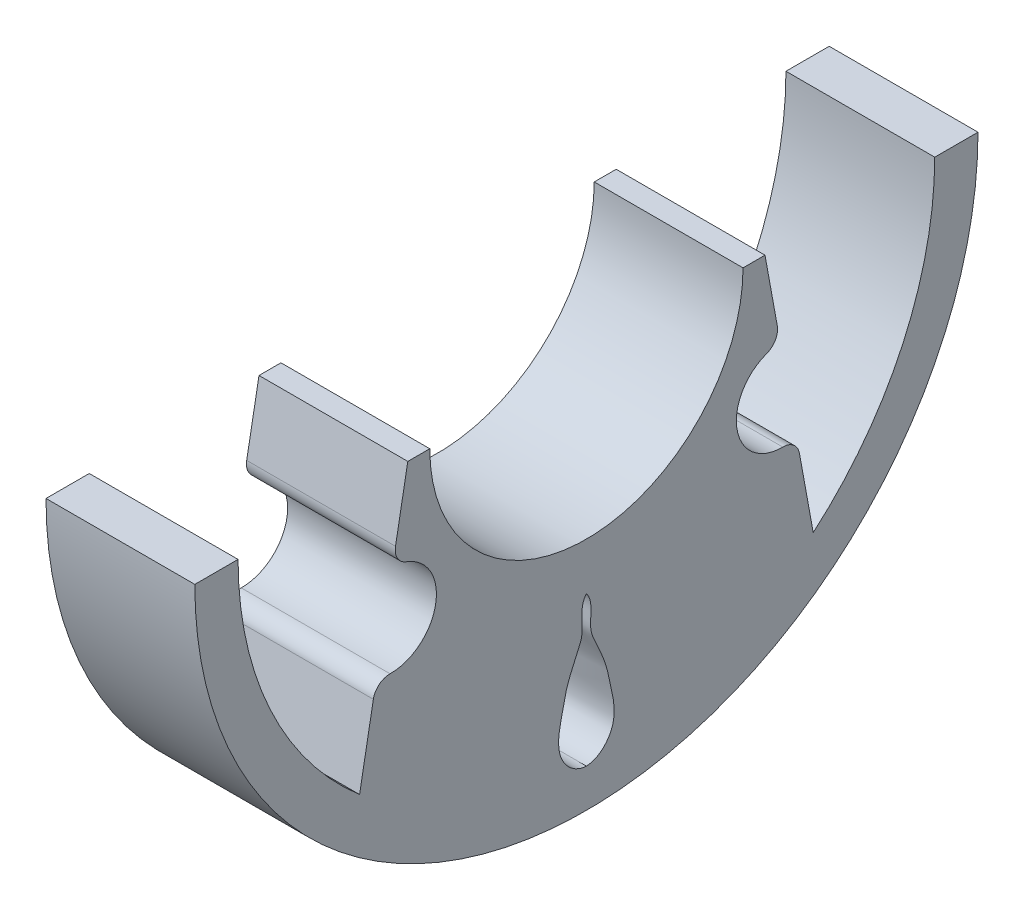
SolidWorks part; units mm, degrees
ref_plane "Front Plane" through (0, 0, 0) normal (0, 0, 1) x (1, 0, 0)
ref_plane "Top Plane" through (0, 0, 0) normal (0, 1, 0) x (1, 0, 0)
ref_plane "Right Plane" through (0, 0, 0) normal (1, 0, 0) x (0, 0, -1)
ref_plane "Plane1" through (0, 0, 0) normal (-1, 0, 0) x (0, -1, 0)
sketch "Sketch1" plane through (0, 0, 0) normal (-1, 0, 0) x (0, -1, 0)
  line L0 (17.2095, 48.7478) -> (0, 45.608)
  line L1 (0, 45.608) -> (0, 40)
  line L2 (0, -40) -> (0, -45.608)
  line L3 (0, -45.608) -> (17.2095, -48.7478)
  line L4 (48.2154, -54.4045) -> (67.5109, -57.9248)
  line L5 (0, -88.955) -> (0, -100)
  line L6 (0, 100) -> (0, 88.955)
  line L7 (67.5109, 57.9248) -> (48.2154, 54.4045)
  arc A0 (22, 45.9999) -> (17.2095, 48.7478) centre (17.9777, 44.5373) ccw
  arc A1 (0, 40) -> (0, -40) centre (0, 0) cw
  arc A2 (17.2095, -48.7478) -> (22, -45.9999) centre (17.9777, -44.5373) ccw
  arc A3 (22, -45.9999) -> (44.7038, -50.142) centre (33, -50) cw
  arc A4 (44.7038, -50.142) -> (48.2154, -54.4045) centre (48.9835, -50.194) ccw
  arc A5 (67.5109, -57.9248) -> (0, -88.955) centre (0, 0) cw
  arc A6 (0, -100) -> (0, 100) centre (0, 0) ccw
  arc A7 (0, 88.955) -> (67.5109, 57.9248) centre (0, 0) cw
  arc A8 (48.2154, 54.4045) -> (44.7038, 50.142) centre (48.9835, 50.194) ccw
  arc A9 (44.7038, 50.142) -> (22, 45.9999) centre (33, 50) cw
  spline S0 degree 3 poles (52, 0) (55.0683, 2.3148) (58.8444, 0.2145) (65.5378, 2.9258) (68.8454, 4.8411) (75.9051, 6.1656) (79.4461, 7.4574) (86.6746, 6.5275) (90.0265, 3.6143) (90.1915, 0) knots 0 0 0 0 0.25 0.25 0.5 0.5 0.75 0.75 1 1 1 1
  spline S1 degree 3 poles (90.1915, 0) (90.0265, -3.6143) (86.6746, -6.5275) (79.4461, -7.4574) (75.9051, -6.1656) (68.8454, -4.8411) (65.5378, -2.9258) (58.8444, -0.2145) (55.0683, -2.3148) (52, 0) knots 0 0 0 0 0.25 0.25 0.5 0.5 0.75 0.75 1 1 1 1
extrude "Boss-Extrude1" add sketch "Sketch1" against normal blind 38
